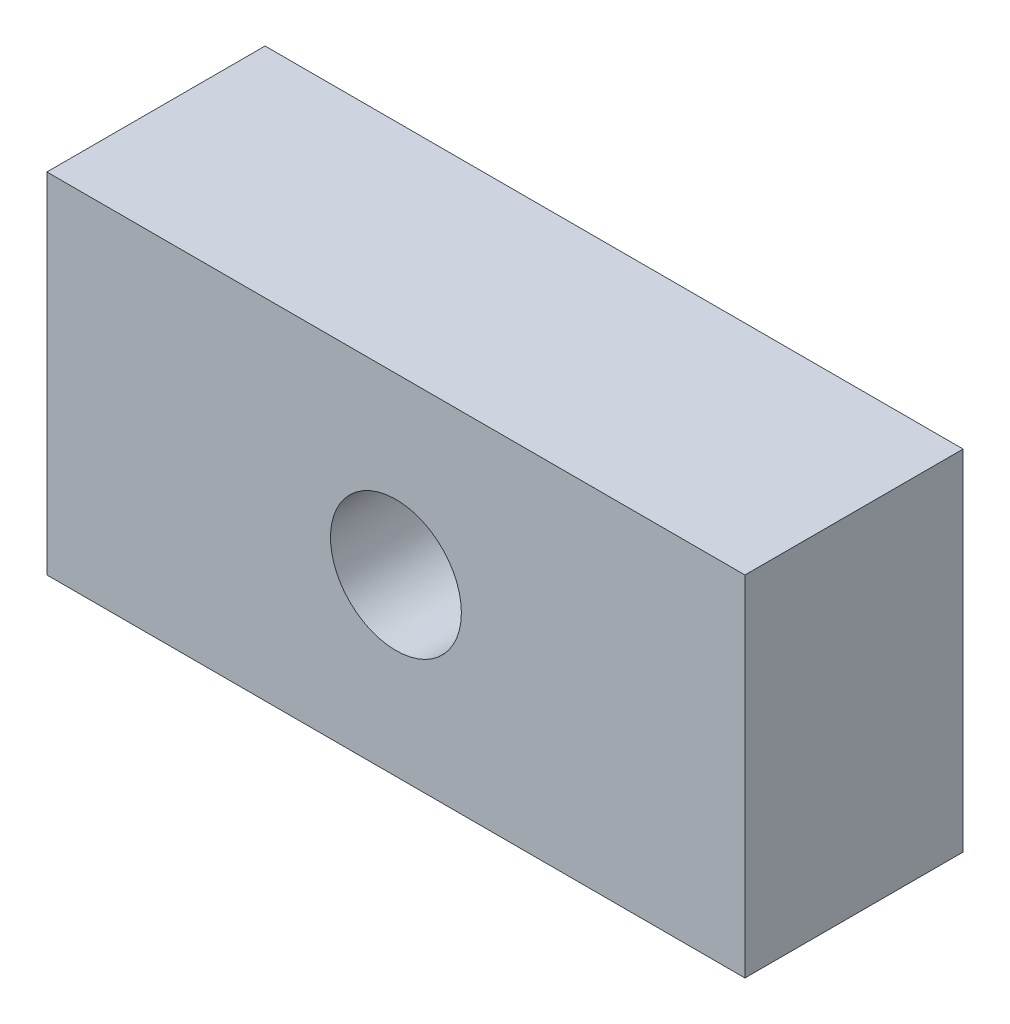
SolidWorks part; units mm, degrees
ref_plane "Front Plane" through (0, 0, 0) normal (0, 0, 1) x (1, 0, 0)
ref_plane "Top Plane" through (0, 0, 0) normal (0, 1, 0) x (1, 0, 0)
ref_plane "Right Plane" through (0, 0, 0) normal (1, 0, 0) x (0, 0, -1)
sketch "Sketch2" plane through (0, 0, 0) normal (0, 0, 1) x (1, 0, 0)
  line L1 (0, 0) -> (101.6, 0)
  line L2 (0, 0) -> (0, 50.8)
  line L3 (0, 50.8) -> (101.6, 50.8)
  line L4 (101.6, 0) -> (101.6, 50.8)
  circle A0 centre (50.8, 25.4) radius 9.525
  dimension "D3" = 25.4
  dimension "D4" = 19.05
  dimension "D1" = 101.6
  dimension "D2" = 50.8
extrude "Boss-Extrude1" add sketch "Sketch2" along normal blind 31.75
